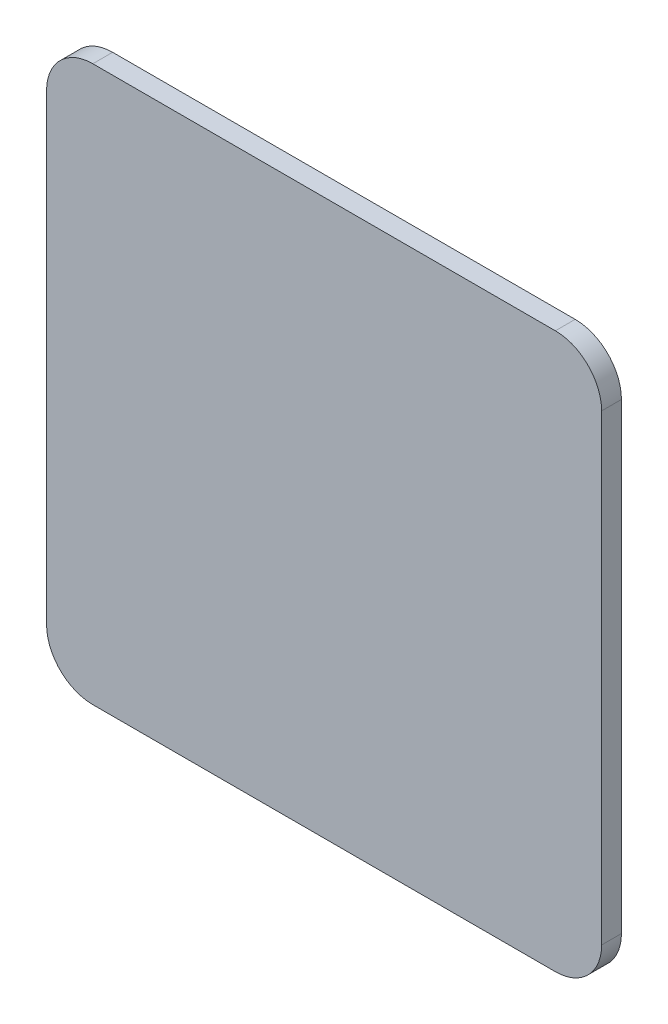
SolidWorks part; units mm, degrees
material "ABS PC"
ref_plane "Front Plane" through (0, 0, 0) normal (0, 0, 1) x (1, 0, 0)
ref_plane "Top Plane" through (0, 0, 0) normal (0, 1, 0) x (1, 0, 0)
ref_plane "Right Plane" through (0, 0, 0) normal (1, 0, 0) x (0, 0, -1)
sketch "Sketch1" plane through (0, 0, 0) normal (0, 0, 1) x (1, 0, 0)
  line L1 (-42, -42) -> (42, -42)
  line L2 (-42, -42) -> (-42, 42)
  line L3 (-42, 42) -> (42, 42)
  line L4 (42, -42) -> (42, 42)
  line L5 (-42, -42) -> (42, 42) construction
  line L6 (-42, 42) -> (42, -42) construction
  point P0 (0, 0)
  dimension "D1" = 84
  dimension "D2" = 84
extrude "Boss-Extrude1" add sketch "Sketch1" along normal blind 3
fillet "Fillet1" radius 7 4 edges at (-42, 42, 1.5) (-42, -42, 1.5) (42, -42, 1.5) (42, 42, 1.5)
